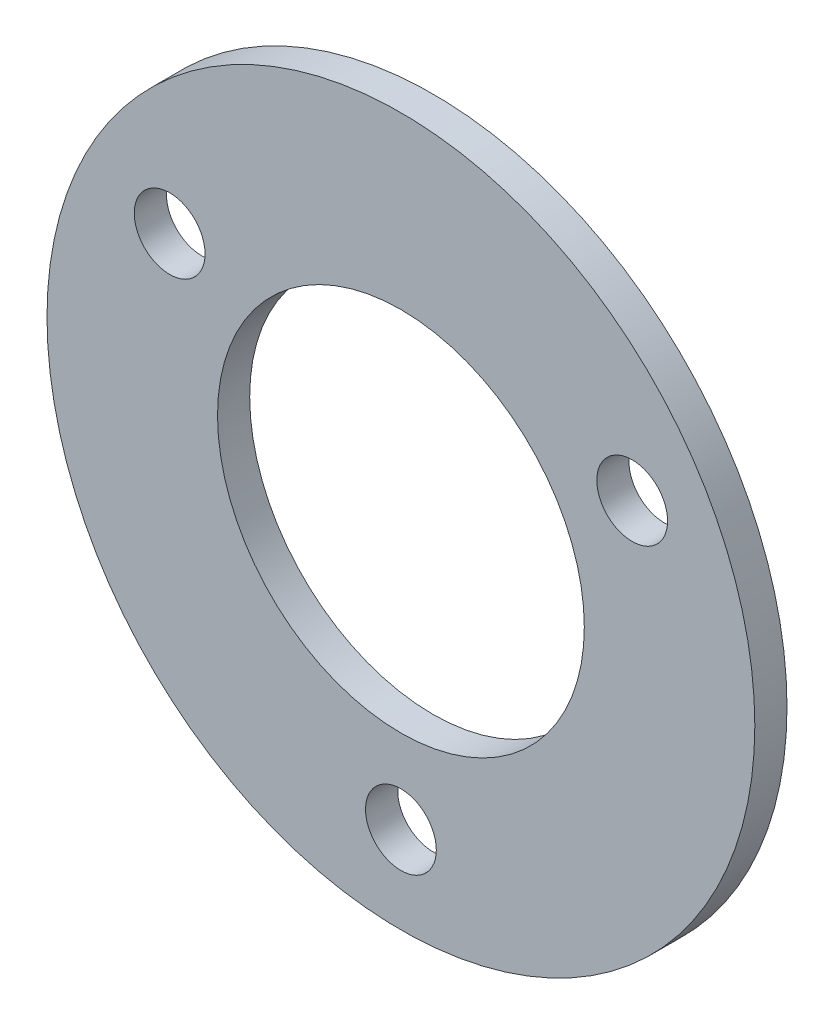
SolidWorks part; units mm, degrees
material "6061-T6 (SS)"
ref_plane "Front Plane" through (0, 0, 0) normal (0, 0, 1) x (1, 0, 0)
ref_plane "Top Plane" through (0, 0, 0) normal (0, 1, 0) x (1, 0, 0)
ref_plane "Right Plane" through (0, 0, 0) normal (1, 0, 0) x (0, 0, -1)
sketch "Sketch1" plane through (0, 0, 0) normal (0, 0, 1) x (1, 0, 0)
  circle A0 centre (0, 0) radius 11
  circle A1 centre (0, 0) radius 5.7
  circle A2 centre (7.188, 4.15) radius 1.1
  circle A3 centre (-7.188, 4.15) radius 1.1
  circle A4 centre (0, -8.3) radius 1.1
extrude "Outer_Race_Cap" add sketch "Sketch1" along normal blind 1
